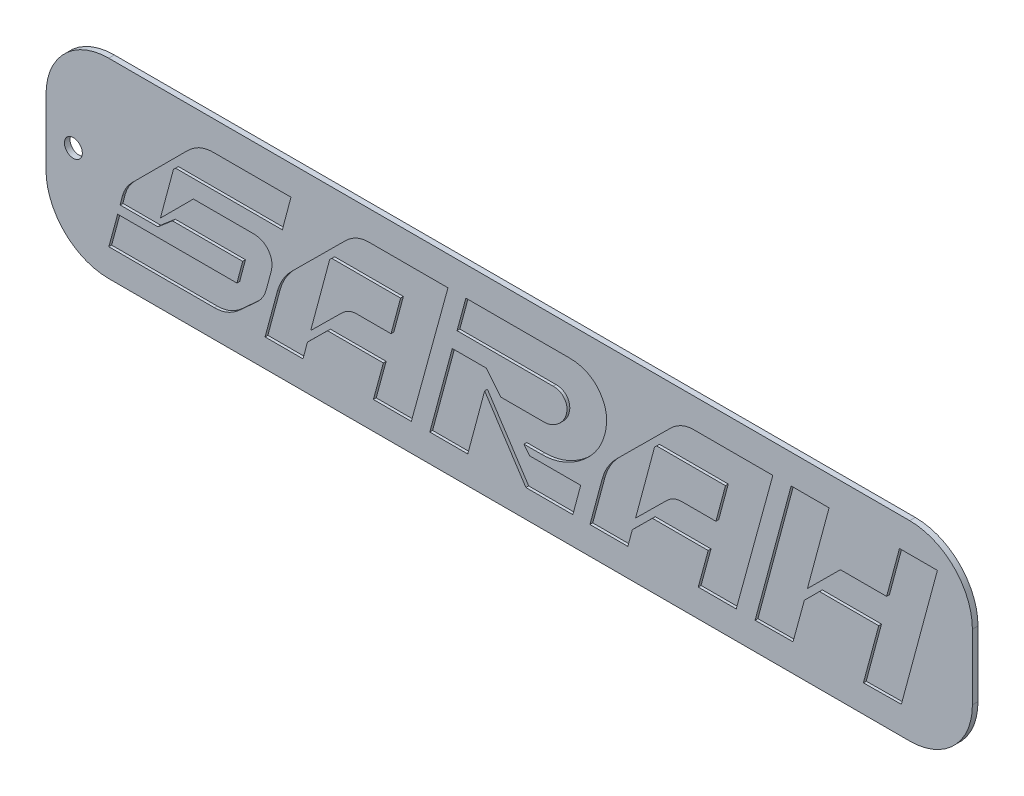
SolidWorks part; units mm, degrees
ref_plane "Front Plane" through (0, 0, 0) normal (0, 0, 1) x (1, 0, 0)
ref_plane "Top Plane" through (0, 0, 0) normal (0, 1, 0) x (1, 0, 0)
ref_plane "Right Plane" through (0, 0, 0) normal (1, 0, 0) x (0, 0, -1)
sketch "Sketch1" plane through (0, 0, 0) normal (0, 0, 1) x (1, 0, 0)
  line L0 (-43.6669, 38.5433) -> (-28.1478, 38.5433) construction
  line L1 (-8.1069, 92.6609) -> (446.0327, 92.6609)
  line L2 (-43.6669, 57.1009) -> (-43.6669, 19.9856)
  line L3 (-8.1069, -15.5744) -> (446.0327, -15.5744)
  line L4 (481.5927, 57.1009) -> (481.5927, 19.9856)
  circle A0 centre (-28.1478, 38.5433) radius 5.08
  arc A1 (446.0327, 92.6609) -> (481.5927, 57.1009) centre (446.0327, 57.1009) cw
  arc A2 (446.0327, -15.5744) -> (481.5927, 19.9856) centre (446.0327, 19.9856) ccw
  arc A3 (-43.6669, 19.9856) -> (-8.1069, -15.5744) centre (-8.1069, 19.9856) ccw
  arc A4 (-8.1069, 92.6609) -> (-43.6669, 57.1009) centre (-8.1069, 57.1009) ccw
  text T0 "Sarah" font "Sterion" height 76.2
  dimension "D1" = 35.56
extrude "Boss-Extrude1" add sketch "Sketch1" along normal blind 3.175
sketch "Sketch2" plane through (0, 0, 3.175) normal (0, 0, 1) x (1, 0, 0)
  text T0 "sarah" font "Sterion" height 76.2
extrude "Cut-Extrude1" cut sketch "Sketch2" against normal blind 1.5875
